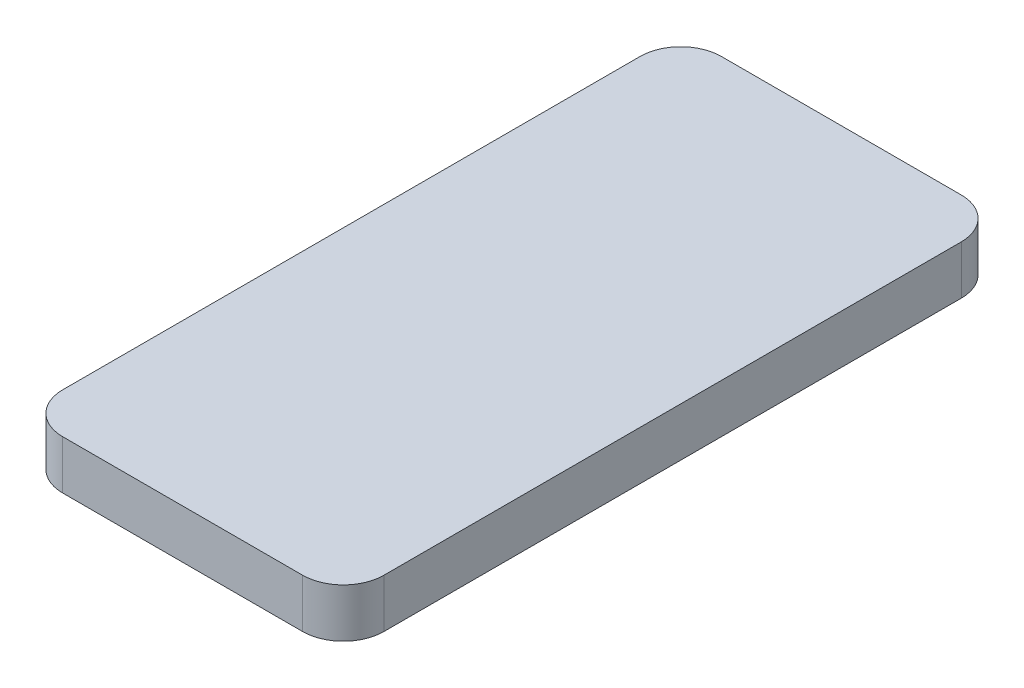
SolidWorks part; units mm, degrees
ref_plane "Front Plane" through (0, 0, 0) normal (0, 0, 1) x (1, 0, 0)
ref_plane "Top Plane" through (0, 0, 0) normal (0, 1, 0) x (1, 0, 0)
ref_plane "Right Plane" through (0, 0, 0) normal (1, 0, 0) x (0, 0, -1)
sketch "Sketch1" plane through (0, 0, 0) normal (0, 1, 0) x (1, 0, 0)
  line L1 (-39.5, 81) -> (39.5, 81)
  line L2 (-39.5, 81) -> (-39.5, -81)
  line L3 (-39.5, -81) -> (39.5, -81)
  line L4 (39.5, 81) -> (39.5, -81)
  line L5 (-39.5, 81) -> (39.5, -81) construction
  line L6 (-39.5, -81) -> (39.5, 81) construction
  point P0 (0, 0)
  dimension "D1" = 162
  dimension "D2" = 79
extrude "Boss-Extrude1" add sketch "Sketch1" along normal blind 12
fillet "Fillet1" radius 10 4 edges at (-39.5, 6, -81) (39.5, 6, -81) (-39.5, 6, 81) (39.5, 6, 81)
